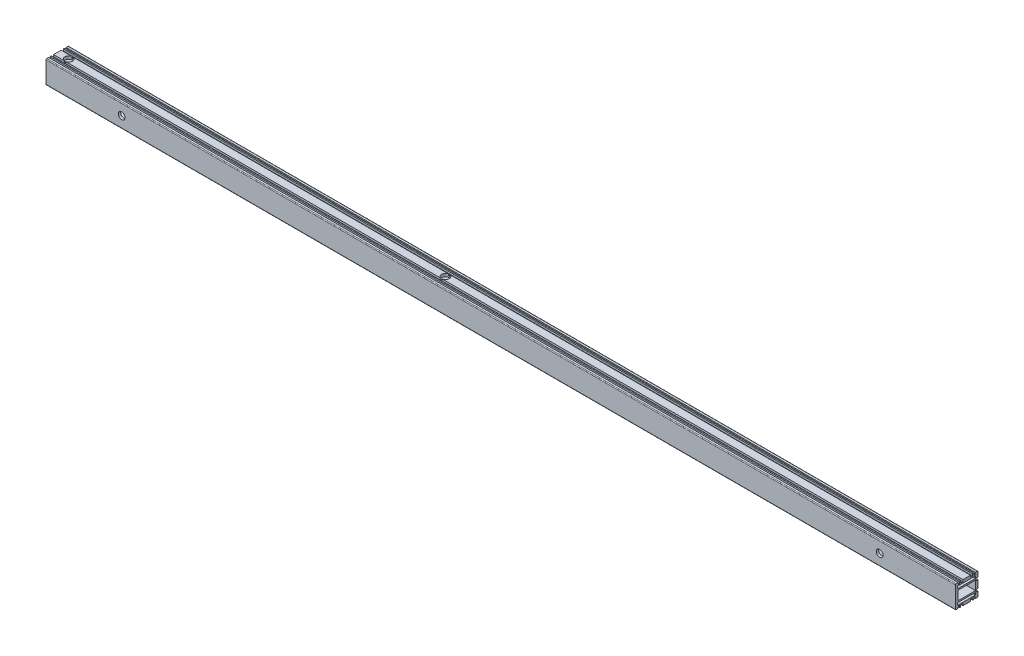
SolidWorks part; units mm, degrees
ref_plane "前视基准面" through (0, 0, 0) normal (0, 0, 1) x (1, 0, 0)
ref_plane "上视基准面" through (0, 0, 0) normal (0, 1, 0) x (1, 0, 0)
ref_plane "右视基准面" through (0, 0, 0) normal (1, 0, 0) x (0, 0, -1)
sketch "草图1" plane through (0, 0, 0) normal (1, 0, 0) x (0, 0, -1)
  line L0 (-15, 15) -> (15, -15) construction
  line L1 (-14, 15) -> (-11.5, 15)
  line L2 (-15, 14) -> (-15, -14)
  line L3 (-14, -15) -> (-11.5, -15)
  line L4 (15, 14) -> (15, 8)
  line L5 (15, 15) -> (-15, -15) construction
  line L6 (-11.5, 15) -> (-11.5, 13.5)
  line L7 (-11.5, 13.5) -> (-11.4, 13.5)
  line L8 (-11, 13.1) -> (-11, 12)
  line L9 (-11, 12) -> (-9.5, 12)
  line L10 (-9.5, 12) -> (-9.5, 15)
  line L11 (-9.5, 15) -> (-8, 15)
  line L12 (-8, 15) -> (-8, 12.5)
  line L13 (-8, 12.5) -> (-5, 12.5)
  line L14 (-5, 12.5) -> (-5, 15)
  line L15 (-5, 15) -> (5, 15)
  line L16 (0, 21.5201) -> (0, -18.309) construction
  line L17 (0, 55) -> (0, -55) construction
  line L18 (5, 12.5) -> (5, 15)
  line L19 (8, 12.5) -> (5, 12.5)
  line L20 (8, 15) -> (8, 12.5)
  line L21 (9.5, 15) -> (8, 15)
  line L22 (9.5, 12) -> (9.5, 15)
  line L23 (11, 12) -> (9.5, 12)
  line L24 (11, 13.1) -> (11, 12)
  line L25 (11.5, 13.5) -> (11.4, 13.5)
  line L26 (11.5, 15) -> (11.5, 13.5)
  line L27 (8, 15) -> (9.5, 15)
  line L28 (11.5, 15) -> (14, 15)
  line L29 (-19.8303, 0) -> (22.13, 0) construction
  line L30 (55, 0) -> (-55, 0) construction
  line L31 (8, -15) -> (9.5, -15)
  line L32 (11.5, -15) -> (11.5, -13.5)
  line L33 (11.5, -13.5) -> (11.4, -13.5)
  line L34 (11, -13.1) -> (11, -12)
  line L35 (11, -12) -> (9.5, -12)
  line L36 (9.5, -12) -> (9.5, -15)
  line L37 (9.5, -15) -> (8, -15)
  line L38 (8, -15) -> (8, -12.5)
  line L39 (8, -12.5) -> (5, -12.5)
  line L40 (5, -12.5) -> (5, -15)
  line L41 (-5, -15) -> (5, -15)
  line L42 (-5, -12.5) -> (-5, -15)
  line L43 (-8, -12.5) -> (-5, -12.5)
  line L44 (-8, -15) -> (-8, -12.5)
  line L45 (-9.5, -15) -> (-8, -15)
  line L46 (-9.5, -12) -> (-9.5, -15)
  line L47 (-11, -12) -> (-9.5, -12)
  line L48 (-11, -13.1) -> (-11, -12)
  line L49 (-11.5, -13.5) -> (-11.4, -13.5)
  line L50 (-11.5, -15) -> (-11.5, -13.5)
  line L51 (-9.5, -15) -> (-8, -15)
  line L52 (-5, -15) -> (5, -15)
  line L53 (8, -15) -> (9.5, -15)
  line L54 (11.5, -15) -> (14, -15)
  line L55 (15, 8) -> (12.5, 8)
  line L56 (12.5, 8) -> (12.5, 5)
  line L57 (12.5, 5) -> (15, 5)
  line L58 (12.5, -5) -> (15, -5)
  line L59 (12.5, -8) -> (12.5, -5)
  line L60 (15, -8) -> (12.5, -8)
  line L61 (15, 5) -> (15, -5)
  line L62 (15, -8) -> (15, -14)
  line L63 (12, -10.5) -> (12, -8.5)
  line L64 (-11.5, 11) -> (11.5, 11)
  line L65 (-12, 10.5) -> (-12, 8.5)
  line L66 (-11.5, 8) -> (11.5, 8)
  line L67 (12, 10.5) -> (12, 8.5)
  line L68 (-11.5, -8) -> (11.5, -8)
  line L69 (-12, -10.5) -> (-12, -8.5)
  line L70 (-11.5, -11) -> (11.5, -11)
  line L72 (-11.75, 6) -> (11.75, 6)
  line L73 (-11.75, 6) -> (-11.75, -6)
  line L74 (-11.75, -6) -> (11.75, -6)
  line L75 (11.75, 6) -> (11.75, -6)
  arc A0 (12, 8.5) -> (11.5, 8) centre (11.5, 8.5) cw
  arc A1 (11.5, 11) -> (12, 10.5) centre (11.5, 10.5) cw
  arc A2 (-11.5, 11) -> (-12, 10.5) centre (-11.5, 10.5) ccw
  arc A3 (-11.5, 8) -> (-12, 8.5) centre (-11.5, 8.5) cw
  arc A4 (-11, -13.1) -> (-11.4, -13.5) centre (-11.4, -13.1) cw
  arc A5 (11.4, -13.5) -> (11, -13.1) centre (11.4, -13.1) cw
  arc A6 (11.4, 13.5) -> (11, 13.1) centre (11.4, 13.1) ccw
  arc A7 (-11, 13.1) -> (-11.4, 13.5) centre (-11.4, 13.1) ccw
  arc A8 (-11.5, -8) -> (-12, -8.5) centre (-11.5, -8.5) ccw
  arc A9 (-11.5, -11) -> (-12, -10.5) centre (-11.5, -10.5) cw
  arc A10 (11.5, -11) -> (12, -10.5) centre (11.5, -10.5) ccw
  arc A11 (12, -8.5) -> (11.5, -8) centre (11.5, -8.5) ccw
  arc A12 (14, 15) -> (15, 14) centre (14, 14) cw
  arc A13 (14, -15) -> (15, -14) centre (14, -14) ccw
  arc A14 (-15, -14) -> (-14, -15) centre (-14, -14) ccw
  arc A15 (-15, 14) -> (-14, 15) centre (-14, 14) cw
  point P69 (12, 11)
  point P72 (-12, 11)
  point P77 (-11, -13.5)
  point P80 (11, -13.5)
  point P83 (11, 13.5)
  point P86 (-11, 13.5)
  point P99 (-12, -11)
  point P100 (12, -11)
  dimension "D17" = 0.5
  dimension "D18" = 0.4
  dimension "D21" = 1
  dimension "D1" = 3.5
  dimension "D2" = 1.5
  dimension "D3" = 0.5
  dimension "D4" = 1.5
  dimension "D5" = 3
  dimension "D6" = 30
  dimension "D7" = 30
  dimension "D8" = 1.5
  dimension "D9" = 2.5
  dimension "D10" = 3
  dimension "D11" = 2.5
  dimension "D12" = 7
  dimension "D13" = 3
  dimension "D14" = 4
  dimension "D15" = 3
  dimension "D16" = 24
  dimension "D19" = 23.5
  dimension "D20" = 12
extrude "凸台-拉伸1" add sketch "草图1" along normal mid plane 1202 contours A15 L2 A14 L3 L50 L49 A4 L48 L47 L46 L45 L44 L43 L42 L41 L40 L39 L38 L31 L36 L35 L34 A5 L33 L32 L54 A13 L62 L60 L59 L58 L61 L57 L56 L55 L4 A12 L28 L26 L25 A6 L24 L23 L22 L21 L20 L19 L18 L15 L14 L13
hole_wizard "M6 螺纹孔1" positions "草图3" profile "草图2" tap size "M6" standard "GB"
sketch "草图3" plane through (0, 0, -15) normal (0, 0, -1) x (-1, 0, 0)
  line L0 (-571, -9) -> (-571, 9) construction
  line L1 (-601, 15) -> (601, 15) construction
  point P0 (-551, 0)
  point P1 (-536, 0)
  point P4 (536, 0)
  point P7 (551, 0)
  dimension "D1" = 20
  dimension "D2" = 15
sketch "草图2" plane through (551, 0, -15) normal (1, 0, 0) x (0, 1, 0)
  line L0 (0, 0) -> (0, 16.5022)
  line L1 (0, 16.5022) -> (2.5, 15)
  line L2 (2.5, 15) -> (2.5, 0)
  line L5 (2.5, 0) -> (0, 0)
  line L10 (0, 16.5022) -> (-2.5, 15) construction
  line L11 (0, -6.35) -> (0, 107.95) construction
  dimension "螺纹孔钻头直径" = 5
  dimension "螺纹孔钻头深度" = 15
  dimension "导头角度" = 118
cosmetic thread "孔螺蚊线1" parameters "D1"=3.25, "D2"=6
cosmetic thread "孔螺蚊线2" parameters "D1"=3.25, "D2"=6
cosmetic thread "孔螺蚊线3" parameters "D1"=3.25, "D2"=6
cosmetic thread "孔螺蚊线4" parameters "D1"=3.25, "D2"=6
hole_wizard "M6 螺纹孔2" positions "草图5" profile "草图4" tap size "M6" standard "GB"
sketch "草图5" plane through (0, -15, 0) normal (0, -1, 0) x (1, 0, 0)
  line L0 (571, -9) -> (571, 9) construction
  line L1 (601, -15) -> (-601, -15) construction
  point P0 (551, 0)
  point P1 (536, 0)
  point P4 (299, 0)
  point P7 (284, 0)
  point P10 (214, 0)
  point P13 (199, 0)
  point P16 (-536, 0)
  point P19 (-551, 0)
  dimension "D1" = 20
  dimension "D2" = 15
sketch "草图4" plane through (551, -15, 0) normal (1, 0, 0) x (0, 0, -1)
  line L0 (0, 0) -> (0, 16.5022)
  line L1 (0, 16.5022) -> (2.5, 15)
  line L2 (2.5, 15) -> (2.5, 0)
  line L5 (2.5, 0) -> (0, 0)
  line L10 (0, 16.5022) -> (-2.5, 15) construction
  line L11 (0, -6.35) -> (0, 107.95) construction
  dimension "螺纹孔钻头直径" = 5
  dimension "螺纹孔钻头深度" = 15
  dimension "导头角度" = 118
cosmetic thread "孔螺蚊线5" parameters "D1"=9, "D2"=6
cosmetic thread "孔螺蚊线6" parameters "D1"=9, "D2"=6
cosmetic thread "孔螺蚊线7" parameters "D1"=9, "D2"=6
cosmetic thread "孔螺蚊线8" parameters "D1"=9, "D2"=6
cosmetic thread "孔螺蚊线9" parameters "D1"=9, "D2"=6
cosmetic thread "孔螺蚊线10" parameters "D1"=9, "D2"=6
cosmetic thread "孔螺蚊线11" parameters "D1"=9, "D2"=6
cosmetic thread "孔螺蚊线12" parameters "D1"=9, "D2"=6
sketch "草图6" plane through (0, -15, 0) normal (0, -1, 0) x (1, 0, 0)
  circle A0 centre (-586, 0) radius 5.05
  circle A1 centre (-88, 0) radius 5.05
  dimension "D1" = 10.1
extrude "切除-拉伸1" cut sketch "草图6" against normal through all
hole_wizard "M4 螺纹孔1" positions "草图8" profile "草图7" tap size "M4" standard "GB"
sketch "草图8" plane through (0, -15, 0) normal (0, -1, 0) x (1, 0, 0)
  line L0 (601, -15) -> (-601, -15) construction
  line L1 (-601, 5) -> (-601, -5) construction
  point P0 (-489, 0)
  point P1 (-329, 0)
  point P3 (-169, 0)
  point P5 (-9, 0)
  point P7 (151, 0)
  dimension "D1" = 15
  dimension "D2" = 112
  dimension "D3" = 160
  dimension "D4" = 160
  dimension "D5" = 160
  dimension "D6" = 160
sketch "草图7" plane through (-489, -15, 0) normal (1, 0, 0) x (0, 0, -1)
  line L0 (0, 0) -> (0, 11.0914)
  line L1 (0, 11.0914) -> (1.65, 10.1)
  line L2 (1.65, 10.1) -> (1.65, 0)
  line L5 (1.65, 0) -> (0, 0)
  line L10 (0, 11.0914) -> (-1.65, 10.1) construction
  line L11 (0, -6.35) -> (0, 107.95) construction
  dimension "螺纹孔钻头直径" = 3.3
  dimension "螺纹孔钻头深度" = 10.1
  dimension "导头角度" = 118
cosmetic thread "孔螺蚊线13" parameters "D1"=8, "D2"=4
cosmetic thread "孔螺蚊线14" parameters "D1"=8, "D2"=4
cosmetic thread "孔螺蚊线15" parameters "D1"=8, "D2"=4
cosmetic thread "孔螺蚊线16" parameters "D1"=8, "D2"=4
cosmetic thread "孔螺蚊线17" parameters "D1"=8, "D2"=4
sketch "草图9" plane through (0, 0, 15) normal (0, 0, 1) x (1, 0, 0)
  line L0 (601, 14) -> (601, -14) construction
  line L1 (-601, 14) -> (-601, -14) construction
  line L2 (-88.7089, 15) -> (-585.2911, 15) construction
  circle A0 centre (501, 0) radius 4.5
  circle A1 centre (-501, 0) radius 4.5
  dimension "D3" = 9
  dimension "D1" = 100
  dimension "D2" = 100
  dimension "D4" = 15
extrude "切除-拉伸2" cut sketch "草图9" against normal through all
hole_wizard "M4 螺纹孔2" positions "草图11" profile "草图10" tap size "M4" standard "GB"
sketch "草图11" plane through (0, 0, -15) normal (0, 0, -1) x (-1, 0, 0)
  line L0 (-601, 15) -> (87.2911, 15) construction
  circle A0 centre (501, 0) radius 4.5 construction
  point P1 (-454, 0)
  point P3 (-259, 0)
  point P5 (-64, 0)
  point P7 (131, 0)
  point P9 (326, 0)
  dimension "D1" = 15
  dimension "D2" = 195
  dimension "D3" = 195
  dimension "D4" = 195
  dimension "D5" = 195
  dimension "D7" = 175
sketch "草图10" plane through (454, 0, -15) normal (1, 0, 0) x (0, 1, 0)
  line L0 (0, 0) -> (0, 11.0914)
  line L1 (0, 11.0914) -> (1.65, 10.1)
  line L2 (1.65, 10.1) -> (1.65, 0)
  line L5 (1.65, 0) -> (0, 0)
  line L10 (0, 11.0914) -> (-1.65, 10.1) construction
  line L11 (0, -6.35) -> (0, 107.95) construction
  dimension "螺纹孔钻头直径" = 3.3
  dimension "螺纹孔钻头深度" = 10.1
  dimension "导头角度" = 118
cosmetic thread "孔螺蚊线18" parameters "D1"=3.25, "D2"=4
cosmetic thread "孔螺蚊线19" parameters "D1"=3.25, "D2"=4
cosmetic thread "孔螺蚊线20" parameters "D1"=3.25, "D2"=4
cosmetic thread "孔螺蚊线21" parameters "D1"=3.25, "D2"=4
cosmetic thread "孔螺蚊线22" parameters "D1"=3.25, "D2"=4
